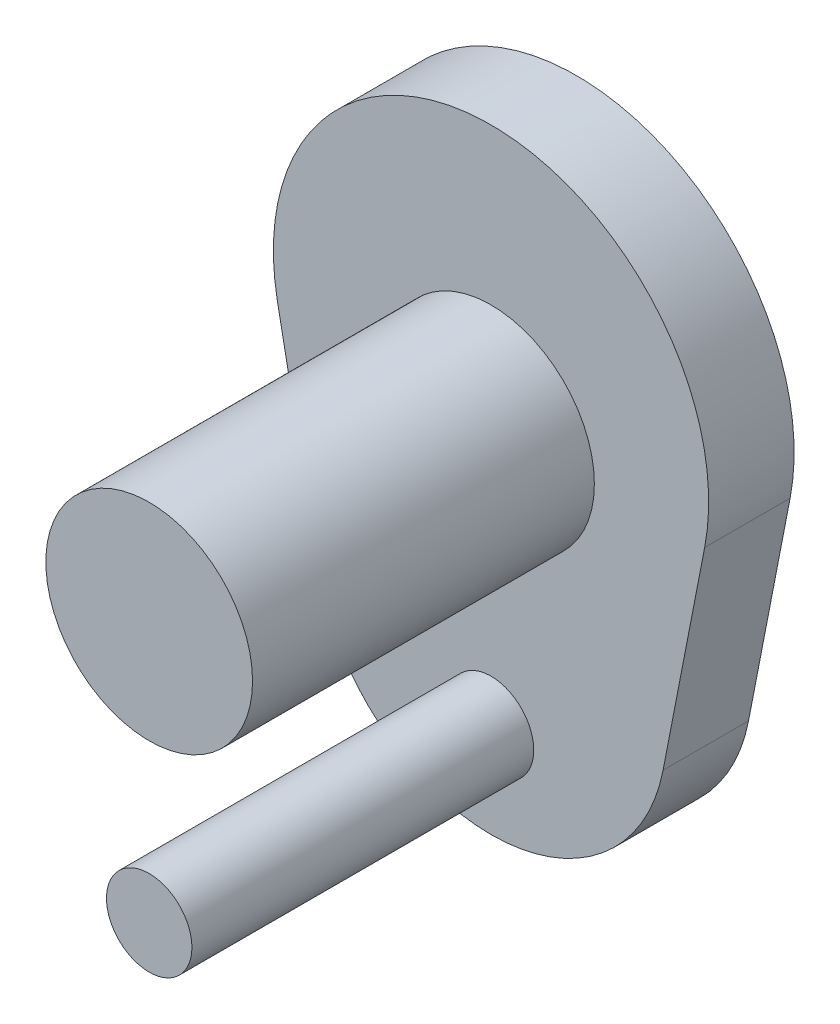
SolidWorks part; units mm, degrees
ref_plane "Front Plane" through (0, 0, 0) normal (0, 0, 1) x (1, 0, 0)
ref_plane "Top Plane" through (0, 0, 0) normal (0, 1, 0) x (1, 0, 0)
ref_plane "Right Plane" through (0, 0, 0) normal (1, 0, 0) x (0, 0, -1)
sketch "Sketch1" plane through (0, 0, 0) normal (0, 0, 1) x (1, 0, 0)
  circle A0 centre (0, 0) radius 15.3591
  dimension "D1" = 30.7181
extrude "Boss-Extrude1" add sketch "Sketch1" along normal blind 50.8 contours A0
sketch "Sketch2" plane through (0, 0, 0) normal (0, 0, -1) x (-1, 0, 0)
  line L0 (-31.75, 0) -> (-25.5701, -31.75)
  line L1 (31.75, 0) -> (25.5701, -31.75)
  arc A0 (-31.75, 0) -> (31.75, 0) centre (0, 6.1799) cw
  arc A1 (-25.5701, -31.75) -> (25.5701, -31.75) centre (0, -26.773) ccw
extrude "Boss-Extrude2" add sketch "Sketch2" along normal blind 12.7
sketch "Sketch3" plane through (0, 0, 0) normal (0, 0, 1) x (1, 0, 0)
  circle A0 centre (0, -38.7777) radius 6.35
  dimension "D1" = 12.7
extrude "Boss-Extrude3" add sketch "Sketch3" along normal blind 50.8
